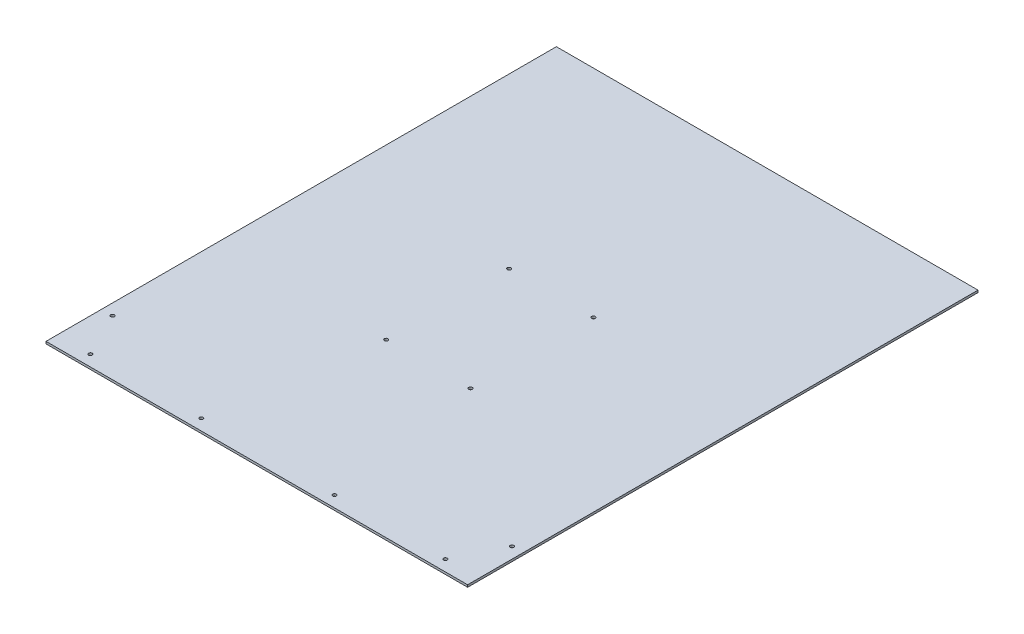
SolidWorks part; units mm, degrees
ref_plane "Front Plane" through (0, 0, 0) normal (0, 0, 1) x (1, 0, 0)
ref_plane "Top Plane" through (0, 0, 0) normal (0, 1, 0) x (1, 0, 0)
ref_plane "Right Plane" through (0, 0, 0) normal (1, 0, 0) x (0, 0, -1)
sketch "Sketch1" plane through (0, 0, 0) normal (0, 1, 0) x (1, 0, 0)
  line L1 (-475, 575) -> (475, 575)
  line L2 (-475, 575) -> (-475, -575)
  line L3 (-475, -575) -> (475, -575)
  line L4 (475, 575) -> (475, -575)
  line L5 (-475, 575) -> (475, -575) construction
  line L6 (-475, -575) -> (475, 575) construction
  point P0 (0, 0)
  dimension "D1" = 1150
  dimension "D2" = 950
extrude "Boss-Extrude1" add sketch "Sketch1" along normal blind 5
sketch "Sketch2" plane through (0, 5, 0) normal (0, 1, 0) x (1, 0, 0)
  line L0 (0, 575) -> (0, -575) construction
  line L1 (-475, 575) -> (475, 575) construction
  line L2 (-475, -575) -> (475, -575) construction
  line L3 (-475, -50) -> (475, -50) construction
  line L4 (-475, 575) -> (-475, -575) construction
  line L5 (475, 575) -> (475, -575) construction
  circle A0 centre (95, 88.5) radius 4
  circle A1 centre (-95, 88.5) radius 4
  circle A2 centre (95, -188.5) radius 4
  circle A3 centre (-95, -188.5) radius 4
  dimension "D2" = 8
  dimension "D1" = 625
  dimension "D3" = 95
  dimension "D4" = 138.5
extrude "Cut-Extrude1" cut sketch "Sketch2" against normal through all
sketch "Sketch3" plane through (0, 0, 0) normal (0, -1, 0) x (1, 0, 0)
  line L0 (0, 575) -> (0, 550) construction
  line L1 (-475, 575) -> (475, 575) construction
  line L2 (-400, 550) -> (400, 550) construction
  line L3 (-475, -575) -> (475, -575) construction
  circle A0 centre (-400, 550) radius 4
  circle A1 centre (-450, 450) radius 4
  circle A2 centre (-150, 550) radius 4
  circle A3 centre (450, 450) radius 4
  circle A4 centre (150, 550) radius 4
  circle A5 centre (400, 550) radius 4
  dimension "D4" = 8
  dimension "D1" = 400
  dimension "D2" = 450
  dimension "D3" = 1125
  dimension "D5" = 100
  dimension "D6" = 150
extrude "Cut-Extrude2" cut sketch "Sketch3" against normal blind 10
